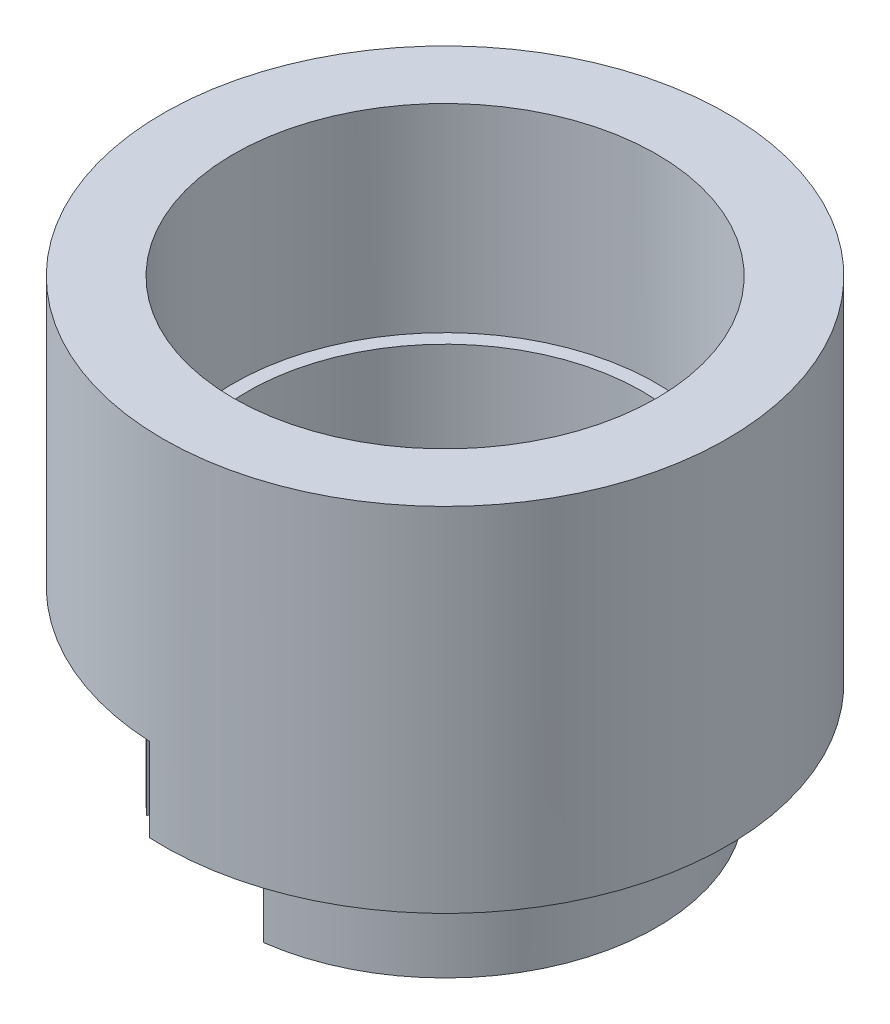
SolidWorks part; units mm, degrees
ref_plane "Plano frontal" through (0, 0, 0) normal (0, 0, 1) x (1, 0, 0)
ref_plane "Plano superior" through (0, 0, 0) normal (0, 1, 0) x (1, 0, 0)
ref_plane "Plano direito" through (0, 0, 0) normal (1, 0, 0) x (0, 0, -1)
sketch "Esboço1" plane through (0, 0, 0) normal (0, 1, 0) x (1, 0, 0)
  circle A0 centre (0, 0) radius 40
  circle A1 centre (0, 0) radius 30
extrude "Ressalto-extrusão1" add sketch "Esboço1" along normal blind 50
ref_plane "Plano1" through (0, 0, 0) normal (0, -1, 0) x (-1, 0, 0)
sketch "Esboço2" plane through (0, 0, 0) normal (0, -1, 0) x (-1, 0, 0)
  line L0 (0, 0) -> (0, -36) construction
  circle A0 centre (0, 0) radius 36 construction
  circle A2 centre (-21.1603, -29.1246) radius 1.5
  circle A3 centre (-34.238, -11.1246) radius 1.5
  circle A4 centre (-34.238, 11.1246) radius 1.5
  circle A7 centre (21.1603, 29.1246) radius 1.5
  circle A8 centre (34.238, 11.1246) radius 1.5
  circle A9 centre (34.238, -11.1246) radius 1.5
  point P25 (0, 0)
extrude "Corte-extrusão1" cut sketch "Esboço2" against normal blind 10
ref_plane "Plano2" through (0, 0, 0) normal (0, -1, 0) x (-1, 0, 0)
sketch "Esboço3" plane through (0, 0, 0) normal (0, -1, 0) x (-1, 0, 0)
  line L0 (16.0924, 28.8103) -> (19.5059, 34.9216)
  line L2 (1.4629, -29.9643) -> (1.9505, -39.9524)
  line L5 (-3.148, 29.8344) -> (-4.1974, 39.7792)
  line L6 (-3.148, 29.8344) -> (-6.3064, 59.7672) construction
  line L7 (30.2939, -13.0873) -> (36.1269, -17.1712)
  line L8 (36.1269, -17.1712) -> (30.2939, -13.0873) construction
  arc A1 (1.4629, -29.9643) -> (-3.148, 29.8344) centre (0, 0) ccw
  arc A2 (1.9505, -39.9524) -> (-4.1974, 39.7792) centre (0, 0) ccw
  arc A3 (30.2939, -13.0873) -> (16.0924, 28.8103) centre (0, 0) ccw
extrude "Corte-extrusão2" cut sketch "Esboço3" against normal blind 11.85 contours L7 A3 L0 A2 L5 A1 L2
ref_plane "Plano3" through (0, 11.85, 0) normal (0, -1, 0) x (-1, 0, 0)
sketch "Esboço4" plane through (0, 11.85, 0) normal (0, -1, 0) x (-1, 0, 0)
  line L0 (-4.0088, -29.7309) -> (-4.7004, -27.6027)
  line L1 (19.9092, -22.4415) -> (19.2303, -20.3518)
  line L2 (-4.0088, -29.7309) -> (-7.1104, -20.1852) construction
  line L3 (16.666, -12.4598) -> (19.9092, -22.4415) construction
  arc A0 (19.9092, -22.4415) -> (-4.0088, -29.7309) centre (0, 0) ccw
  arc A1 (19.2303, -20.3518) -> (-4.7004, -27.6027) centre (0, 0) ccw
extrude "Ressalto-extrusão2" add sketch "Esboço4" along normal blind 26.85 and the other way blind 10
ref_plane "Plano4" through (0, 11.85, 0) normal (0, -1, 0) x (-1, 0, 0)
